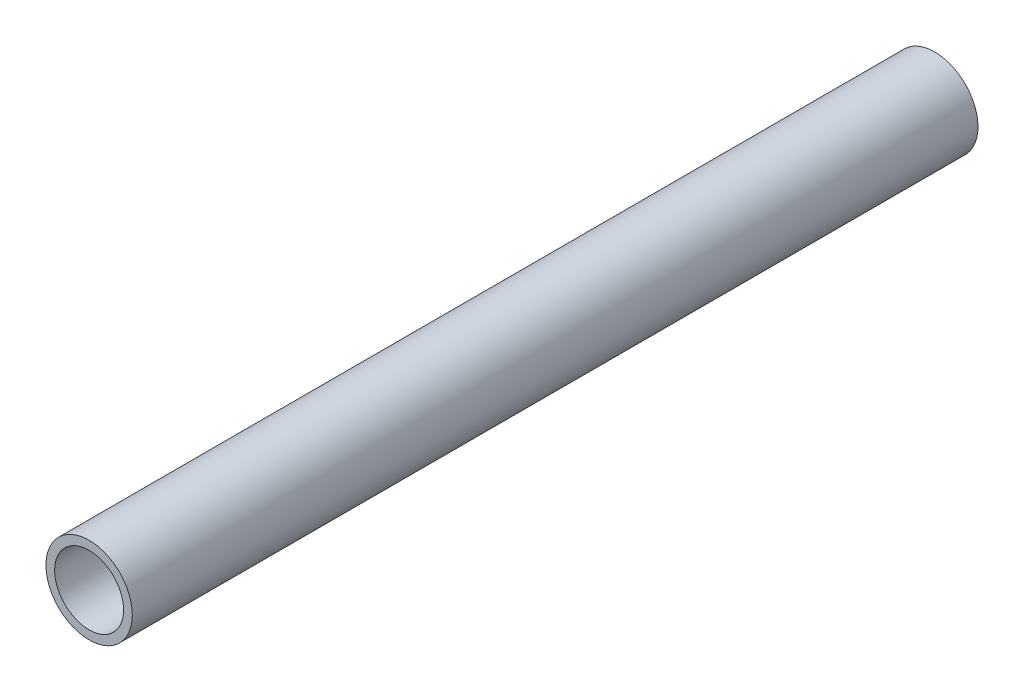
SolidWorks part; units mm, degrees
ref_plane "Front" through (0, 0, 0) normal (0, 0, 1) x (1, 0, 0)
ref_plane "Top" through (0, 0, 0) normal (0, 1, 0) x (1, 0, 0)
ref_plane "Right" through (0, 0, 0) normal (1, 0, 0) x (0, 0, -1)
sketch "Sketch1" plane through (0, 0, 0) normal (0, 0, 1) x (1, 0, 0)
  circle A0 centre (0, 0) radius 16.7005
  circle A1 centre (0, 0) radius 13.3223
  dimension "D1" = 33.401
  dimension "D2" = 26.6446
extrude "Boss-Extrude1" add sketch "Sketch1" along normal mid plane 327
